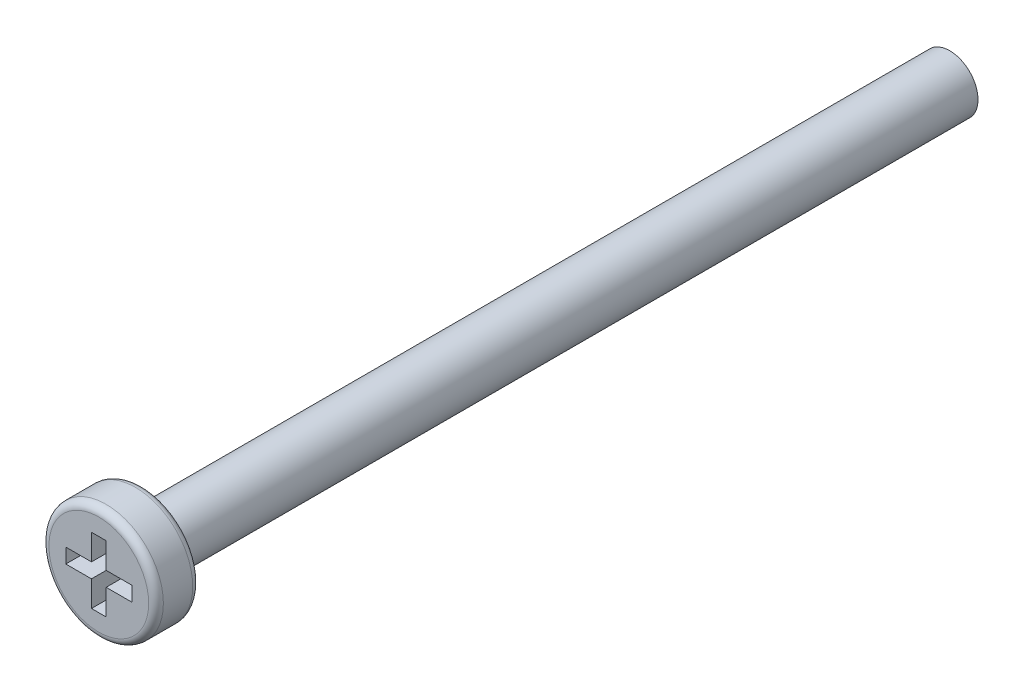
SolidWorks part; units mm, degrees
ref_plane "Plano frontal" through (0, 0, 0) normal (0, 0, 1) x (1, 0, 0)
ref_plane "Plano superior" through (0, 0, 0) normal (0, 1, 0) x (1, 0, 0)
ref_plane "Plano direito" through (0, 0, 0) normal (1, 0, 0) x (0, 0, -1)
sketch "Esboço5" plane through (0, 0, 0) normal (0, 0, 1) x (1, 0, 0)
  circle A0 centre (0, 0) radius 3.9
  dimension "D1" = 7.8
extrude "Ressalto-extrusão2" add sketch "Esboço5" along normal blind 3
sketch "Esboço7" plane through (0, 0, 3) normal (0, 0, 1) x (1, 0, 0)
  line L0 (-0.5, -0.5) -> (-2.25, -0.5)
  line L1 (0.5, 2.25) -> (-0.5, 2.25)
  line L2 (0.5, 2.25) -> (0.5, 0.5)
  line L3 (0.5, -2.25) -> (-0.5, -2.25)
  line L4 (-0.5, 2.25) -> (-0.5, 0.5)
  line L7 (2.25, 0.5) -> (0.5, 0.5)
  line L8 (2.25, 0.5) -> (2.25, -0.5)
  line L9 (2.25, -0.5) -> (0.5, -0.5)
  line L10 (-2.25, 0.5) -> (-2.25, -0.5)
  line L13 (-0.5, -0.5) -> (-0.5, -2.25)
  line L15 (-0.5, 0.5) -> (-2.25, 0.5)
  line L18 (0.5, -0.5) -> (0.5, -2.25)
  point P0 (0, 0)
  point P5 (0, 0)
extrude "Corte-extrusão3" cut sketch "Esboço7" against normal blind 2
fillet "Filete1" radius 0.5 2 edges at (3.9, 0, 0) (3.9, 0, 3)
sketch "Esboço8" plane through (0, 0, 0) normal (0, 0, -1) x (-1, 0, 0)
  circle A0 centre (0, 0) radius 1.925
  dimension "D1" = 3.85
extrude "Ressalto-extrusão3" add sketch "Esboço8" along normal blind 55
